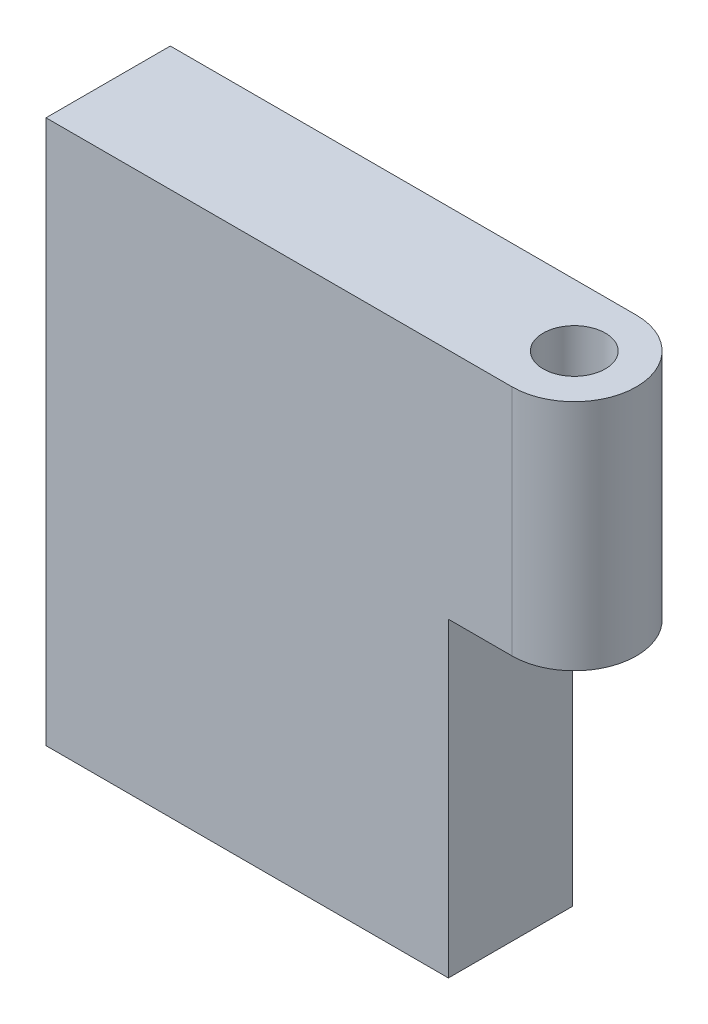
SolidWorks part; units mm, degrees
ref_plane "Front Plane" through (0, 0, 0) normal (0, 0, 1) x (1, 0, 0)
ref_plane "Top Plane" through (0, 0, 0) normal (0, 1, 0) x (1, 0, 0)
ref_plane "Right Plane" through (0, 0, 0) normal (1, 0, 0) x (0, 0, -1)
sketch "Sketch1" plane through (0, 0, 0) normal (0, 1, 0) x (1, 0, 0)
  line L1 (0, -4) -> (-30, -4)
  line L2 (0, -4) -> (0, 4)
  line L3 (0, 4) -> (-30, 4)
  line L4 (-30, -4) -> (-30, 4)
  circle A0 centre (0, 0) radius 4
  point P8 (0, 0)
  dimension "D1" = 30
  dimension "D3" = 8
  dimension "D2" = 8
extrude "Boss-Extrude1" add sketch "Sketch1" along normal blind 15 contours A0 L3 L4 L1 | L2 A0 | L2 A0
sketch "Sketch2" plane through (0, 15, 0) normal (0, 1, 0) x (1, 0, 0)
  circle A0 centre (0, 0) radius 2
extrude "Cut-Extrude1" cut sketch "Sketch2" against normal through all
sketch "Sketch3" plane through (0, 0, 0) normal (0, -1, 0) x (1, 0, 0)
  line L0 (0, -4) -> (-30, -4) construction
  line L1 (-30, 4) -> (-4.1, 4)
  line L2 (-30, 4) -> (-30, -4)
  line L3 (-30, -4) -> (-4.1, -4)
  line L4 (-4.1, 4) -> (-4.1, -4)
  circle A0 centre (0, 0) radius 2 construction
  point P9 (-4.1, 0)
  dimension "D1" = 4.1
extrude "Boss-Extrude2" add sketch "Sketch3" along normal blind 20
